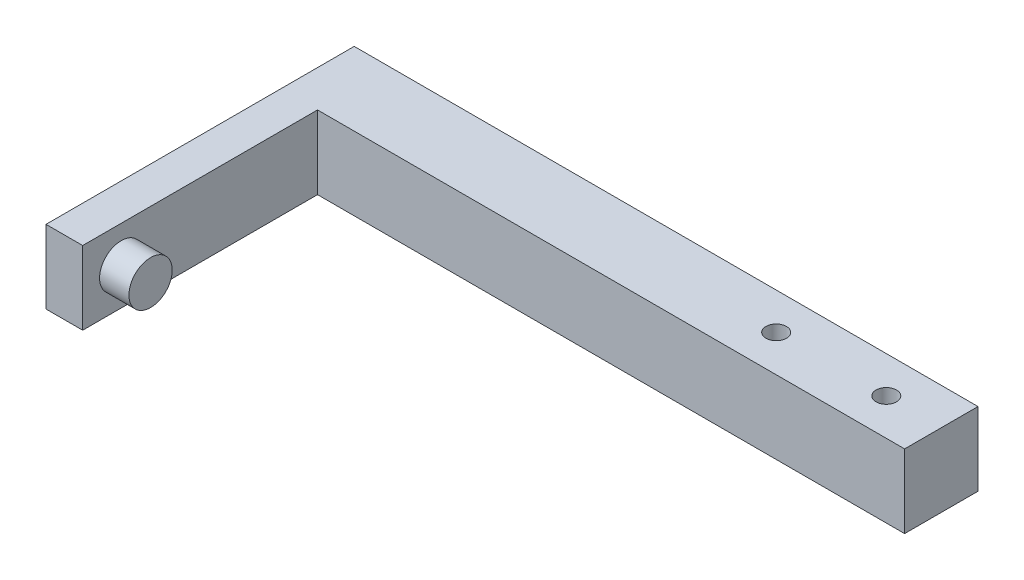
SolidWorks part; units mm, degrees
ref_plane "Front Plane" through (0, 0, 0) normal (0, 0, 1) x (1, 0, 0)
ref_plane "Top Plane" through (0, 0, 0) normal (0, 1, 0) x (1, 0, 0)
ref_plane "Right Plane" through (0, 0, 0) normal (1, 0, 0) x (0, 0, -1)
sketch "Sketch1" plane through (0, 0, 0) normal (0, 1, 0) x (1, 0, 0)
  line L1 (-42.5, 5) -> (42.5, 5)
  line L2 (-42.5, 5) -> (-42.5, -5)
  line L3 (-42.5, -5) -> (42.5, -5)
  line L4 (42.5, 5) -> (42.5, -5)
  point P4 (0, 5)
  point P6 (-42.5, 0)
  dimension "D1" = 10
  dimension "D2" = 85
extrude "Boss-Extrude1" add sketch "Sketch1" along normal blind 10
sketch "Sketch2" plane through (0, 10, 0) normal (0, 1, 0) x (1, 0, 0)
  line L0 (42.5, -5) -> (42.5, 5) construction
  circle A0 centre (35, 0) radius 1.4
  circle A1 centre (20, 0) radius 1.4
  point P4 (42.5, 0)
  dimension "D1" = 2.8
  dimension "D2" = 7.5
  dimension "D3" = 22.5
extrude "Cut-Extrude1" cut sketch "Sketch2" against normal blind 10
sketch "Sketch3" plane through (0, 0, 5) normal (0, 0, 1) x (1, 0, 0)
  line L0 (-42.5, 0) -> (42.5, 0) construction
  line L1 (-42.5, 10) -> (-37.5, 10)
  line L2 (-42.5, 10) -> (-42.5, 0)
  line L3 (-42.5, 0) -> (-37.5, 0)
  line L4 (-37.5, 10) -> (-37.5, 0)
  dimension "D1" = 5
extrude "Boss-Extrude2" add sketch "Sketch3" along normal blind 32
sketch "Sketch4" plane through (-37.5, 0, 0) normal (1, 0, 0) x (0, 0, -1)
  line L0 (-37, 0) -> (-37, 10) construction
  line L1 (-5, 0) -> (-5, 10) construction
  circle A0 centre (-31.75, 5) radius 2.95
  point P4 (-37, 5)
  dimension "D1" = 5.9
  dimension "D2" = 26.75
extrude "Boss-Extrude3" add sketch "Sketch4" along normal blind 4
